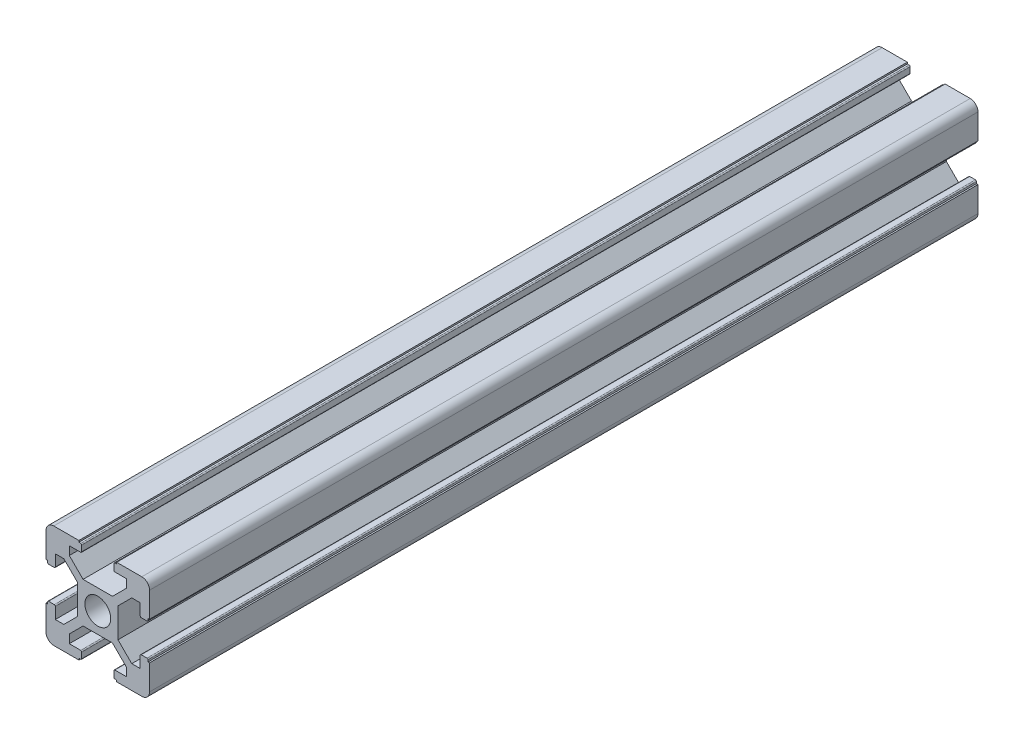
SolidWorks part; units mm, degrees
ref_plane "前视基准面" through (0, 0, 0) normal (0, 0, 1) x (1, 0, 0)
ref_plane "上视基准面" through (0, 0, 0) normal (0, 1, 0) x (1, 0, 0)
ref_plane "右视基准面" through (0, 0, 0) normal (1, 0, 0) x (0, 0, -1)
sketch "草图1" plane through (0, 0, 0) normal (0, 0, 1) x (1, 0, 0)
  line L0 (-17.5, 0) -> (33.5, 0) construction
  line L1 (0, 35.5833) -> (0, -31.0833) construction
  line L2 (3.65, 10) -> (8.5, 10)
  line L3 (10, 10) -> (10, -10) construction
  line L4 (-2.8393, 3.9) -> (2.8393, 3.9)
  line L5 (3.9, 2.8393) -> (3.9, -2.8393)
  line L6 (5.5, 8.2) -> (5.5, 6.5607)
  line L7 (3.9, 3.9) -> (10, 10) construction
  line L8 (4.4303, 3.3697) -> (6.5607, 5.5) construction
  line L9 (3.65, 10) -> (3.65, 8.2)
  line L10 (3.65, 8.2) -> (5.5, 8.2)
  line L11 (3.3697, 4.4303) -> (5.5, 6.5607) construction
  line L12 (5.5, 6.5607) -> (2.8393, 3.9)
  line L13 (6.5607, 5.5) -> (3.9, 2.8393)
  line L14 (3.3697, 4.4303) -> (9.4697, 10.5303) construction
  line L15 (4.4303, 3.3697) -> (10.5303, 9.4697) construction
  line L16 (8.2, 5.5) -> (6.5607, 5.5)
  line L17 (8.2, 3.65) -> (8.2, 5.5)
  line L18 (10, 3.65) -> (10, 8.5)
  line L19 (10, 3.65) -> (8.2, 3.65)
  line L20 (-3.3697, 4.4303) -> (-5.5, 6.5607) construction
  line L21 (-4.4303, 3.3697) -> (-6.5607, 5.5) construction
  line L22 (-3.9, 3.9) -> (-10, 10) construction
  line L23 (-10, 10) -> (-10, -10) construction
  line L24 (-10, 3.65) -> (-8.2, 3.65)
  line L25 (-10, 3.65) -> (-10, 8.5)
  line L26 (-8.2, 3.65) -> (-8.2, 5.5)
  line L27 (-8.2, 5.5) -> (-6.5607, 5.5)
  line L28 (-6.5607, 5.5) -> (-3.9, 2.8393)
  line L29 (-5.5, 6.5607) -> (-2.8393, 3.9)
  line L30 (-3.65, 8.2) -> (-5.5, 8.2)
  line L31 (-3.65, 10) -> (-3.65, 8.2)
  line L32 (-5.5, 8.2) -> (-5.5, 6.5607)
  line L33 (-3.9, 2.8393) -> (-3.9, -2.8393)
  line L34 (-3.65, 10) -> (-8.5, 10)
  line L35 (-3.9, -3.9) -> (-10, -10) construction
  line L36 (-4.4303, -3.3697) -> (-6.5607, -5.5) construction
  line L37 (-3.3697, -4.4303) -> (-5.5, -6.5607) construction
  line L38 (3.3697, -4.4303) -> (5.5, -6.5607) construction
  line L39 (4.4303, -3.3697) -> (6.5607, -5.5) construction
  line L40 (3.9, -3.9) -> (10, -10) construction
  line L41 (-3.65, -10) -> (-8.5, -10)
  line L42 (-5.5, -8.2) -> (-5.5, -6.5607)
  line L43 (-3.65, -10) -> (-3.65, -8.2)
  line L44 (-3.65, -8.2) -> (-5.5, -8.2)
  line L45 (-5.5, -6.5607) -> (-2.8393, -3.9)
  line L46 (-6.5607, -5.5) -> (-3.9, -2.8393)
  line L47 (-8.2, -5.5) -> (-6.5607, -5.5)
  line L48 (-8.2, -3.65) -> (-8.2, -5.5)
  line L49 (-10, -3.65) -> (-10, -8.5)
  line L50 (-10, -3.65) -> (-8.2, -3.65)
  line L51 (10, -3.65) -> (8.2, -3.65)
  line L52 (10, -3.65) -> (10, -8.5)
  line L53 (8.2, -3.65) -> (8.2, -5.5)
  line L54 (8.2, -5.5) -> (6.5607, -5.5)
  line L55 (6.5607, -5.5) -> (3.9, -2.8393)
  line L56 (5.5, -6.5607) -> (2.8393, -3.9)
  line L57 (3.65, -8.2) -> (5.5, -8.2)
  line L58 (3.65, -10) -> (3.65, -8.2)
  line L59 (5.5, -8.2) -> (5.5, -6.5607)
  line L60 (-2.8393, -3.9) -> (2.8393, -3.9)
  line L61 (3.65, -10) -> (8.5, -10)
  circle A0 centre (0, 0) radius 2.5
  arc A1 (-8.5, -10) -> (-10, -8.5) centre (-8.5, -8.5) cw
  arc A2 (10, -8.5) -> (8.5, -10) centre (8.5, -8.5) cw
  arc A3 (8.5, 10) -> (10, 8.5) centre (8.5, 8.5) cw
  arc A4 (-10, 8.5) -> (-8.5, 10) centre (-8.5, 8.5) cw
  point P13 (0, -3.9)
  point P42 (0, 3.9)
  point P43 (-10, 0)
  point P54 (10, 0)
  point P56 (-3.9, 0)
  point P70 (3.9, 0)
  dimension "D3" = 5
  dimension "D10" = 1.5
  dimension "D1" = 7.3
  dimension "D2" = 10
  dimension "D4" = 3.9
  dimension "D5" = 3.9
  dimension "D8" = 1.8
  dimension "D9" = 0.75
  dimension "D6" = 11
  dimension "D7" = 10
  dimension "D11" = 45
  dimension "D12" = 2.8393
extrude "凸台-拉伸2" add sketch "草图1" along normal blind 160 contours L34 A4 L25 L24 L26 L27 L28 L33 L46 L47 L48 L50 L49 A1 L41 L43 L44 L42 L45 L60 L56 L59 L57 L58 L61 A2 L52 L51 L53 L54 L55 L5 L13 L16 L17 L19 L18 A3 L2 L9 L10 L6 L12 L4 L29 L32 L30 L31
sketch "草图3" plane through (0, 0, 160) normal (0, 0, 1) x (1, 0, 0)
  line L0 (-12.6954, 0) -> (11.5012, 0) construction
  line L1 (0, 10.0863) -> (0, -11.0469) construction
  line L2 (-3.65, 8.2) -> (-3.3, 8.2)
  line L3 (3.65, 8.2) -> (3.6528, 8.2568)
  line L4 (-3.1, 8.4) -> (-3.1, 9.5)
  line L5 (3.65, 9.7) -> (3.65, 8.2)
  line L6 (-3.3, 9.7) -> (-3.65, 9.7)
  line L7 (-3.65, 8.2) -> (-3.65, 10) construction
  line L8 (-3.65, 9.7) -> (-3.65, 8.2)
  line L9 (-3.65, 8.2) -> (-3.6528, 8.2568)
  line L10 (3.3, 9.7) -> (3.65, 9.7)
  line L11 (3.1, 8.4) -> (3.1, 9.5)
  line L12 (3.65, 8.2) -> (3.3, 8.2)
  line L13 (3.65, -8.2) -> (3.3, -8.2)
  line L14 (3.1, -8.4) -> (3.1, -9.5)
  line L15 (3.3, -9.7) -> (3.65, -9.7)
  line L16 (-3.65, -8.2) -> (-3.6528, -8.2568)
  line L17 (-3.65, -9.7) -> (-3.65, -8.2)
  line L18 (-3.3, -9.7) -> (-3.65, -9.7)
  line L19 (3.65, -9.7) -> (3.65, -8.2)
  line L20 (-3.1, -8.4) -> (-3.1, -9.5)
  line L21 (3.65, -8.2) -> (3.6528, -8.2568)
  line L22 (-3.65, -8.2) -> (-3.3, -8.2)
  line L23 (0, 0) -> (9.5607, 9.5607) construction
  line L24 (-8.2, -3.65) -> (-8.2, -3.3)
  line L25 (-8.4, -3.1) -> (-9.5, -3.1)
  line L26 (-9.7, -3.3) -> (-9.7, -3.65)
  line L27 (-9.7, -3.65) -> (-8.2, -3.65)
  line L28 (-8.2, -3.65) -> (-8.2568, -3.6528)
  line L29 (8.2, 3.65) -> (8.2, 3.3)
  line L30 (8.4, 3.1) -> (9.5, 3.1)
  line L31 (9.7, 3.3) -> (9.7, 3.65)
  line L32 (9.7, 3.65) -> (8.2, 3.65)
  line L33 (8.2, 3.65) -> (8.2568, 3.6528)
  line L34 (-8.2, 3.65) -> (-8.2568, 3.6528)
  line L35 (-9.7, 3.65) -> (-8.2, 3.65)
  line L36 (-9.7, 3.3) -> (-9.7, 3.65)
  line L37 (-8.4, 3.1) -> (-9.5, 3.1)
  line L38 (-8.2, 3.65) -> (-8.2, 3.3)
  line L39 (8.2, -3.65) -> (8.2568, -3.6528)
  line L40 (9.7, -3.65) -> (8.2, -3.65)
  line L41 (9.7, -3.3) -> (9.7, -3.65)
  line L42 (8.4, -3.1) -> (9.5, -3.1)
  line L43 (8.2, -3.65) -> (8.2, -3.3)
  arc A0 (-3.1, 9.5) -> (-3.3, 9.7) centre (-3.3, 9.5) ccw
  arc A1 (-3.3, 8.2) -> (-3.1, 8.4) centre (-3.3, 8.4) ccw
  arc A2 (3.3, 8.2) -> (3.1, 8.4) centre (3.3, 8.4) cw
  arc A3 (3.1, 9.5) -> (3.3, 9.7) centre (3.3, 9.5) cw
  arc A4 (3.1, -9.5) -> (3.3, -9.7) centre (3.3, -9.5) ccw
  arc A5 (3.3, -8.2) -> (3.1, -8.4) centre (3.3, -8.4) ccw
  arc A6 (-3.3, -8.2) -> (-3.1, -8.4) centre (-3.3, -8.4) cw
  arc A7 (-3.1, -9.5) -> (-3.3, -9.7) centre (-3.3, -9.5) cw
  arc A8 (10, 8.5) -> (8.5, 10) centre (8.5, 8.5) ccw construction
  arc A9 (-9.5, -3.1) -> (-9.7, -3.3) centre (-9.5, -3.3) ccw
  arc A10 (-8.2, -3.3) -> (-8.4, -3.1) centre (-8.4, -3.3) ccw
  arc A11 (9.5, 3.1) -> (9.7, 3.3) centre (9.5, 3.3) ccw
  arc A12 (8.2, 3.3) -> (8.4, 3.1) centre (8.4, 3.3) ccw
  arc A13 (-8.2, 3.3) -> (-8.4, 3.1) centre (-8.4, 3.3) cw
  arc A14 (-9.5, 3.1) -> (-9.7, 3.3) centre (-9.5, 3.3) cw
  arc A15 (8.2, -3.3) -> (8.4, -3.1) centre (8.4, -3.3) cw
  arc A16 (9.5, -3.1) -> (9.7, -3.3) centre (9.5, -3.3) cw
  point P16 (-3.1, 9.7)
  point P19 (-3.1, 8.2)
  point P29 (3.1, 8.2)
  point P30 (3.1, 9.7)
  point P49 (3.1, -9.7)
  point P50 (3.1, -8.2)
  point P51 (-3.1, -8.2)
  point P52 (-3.1, -9.7)
  point P67 (-9.7, -3.1)
  point P68 (-8.2, -3.1)
  point P78 (9.7, 3.1)
  point P79 (8.2, 3.1)
  point P89 (-8.2, 3.1)
  point P90 (-9.7, 3.1)
  point P100 (8.2, -3.1)
  point P101 (9.7, -3.1)
  line M1 (-3.65, -10) -> (-3.65, -8.2)
  line M9 (3.65, -8.2) -> (3.65, -10)
  line M21 (8.2, 3.65) -> (10, 3.65)
  line M25 (3.65, 10) -> (3.65, 8.2)
  line M33 (-3.65, 8.2) -> (-3.65, 10)
  line M37 (-10, 3.65) -> (-8.2, 3.65)
  dimension "D3" = 0.2
  dimension "D1" = 6.2
  dimension "D2" = 1.5
extrude "凸台-拉伸3" add sketch "草图3" against normal blind 160 contours A14 L37 A13 L38 L36 M37 | L2 A1 L4 A0 L6 M33 | A3 L11 A2 L12 L10 M25 | L29 A12 L30 A11 L31 M21 | L13 A5 L14 A4 L15 M9 | A7 L20 A6 L22 L18 M1 | L43 A15 L42 A16 L41 L40 | L24 A10 L25 A9 L26 L27
